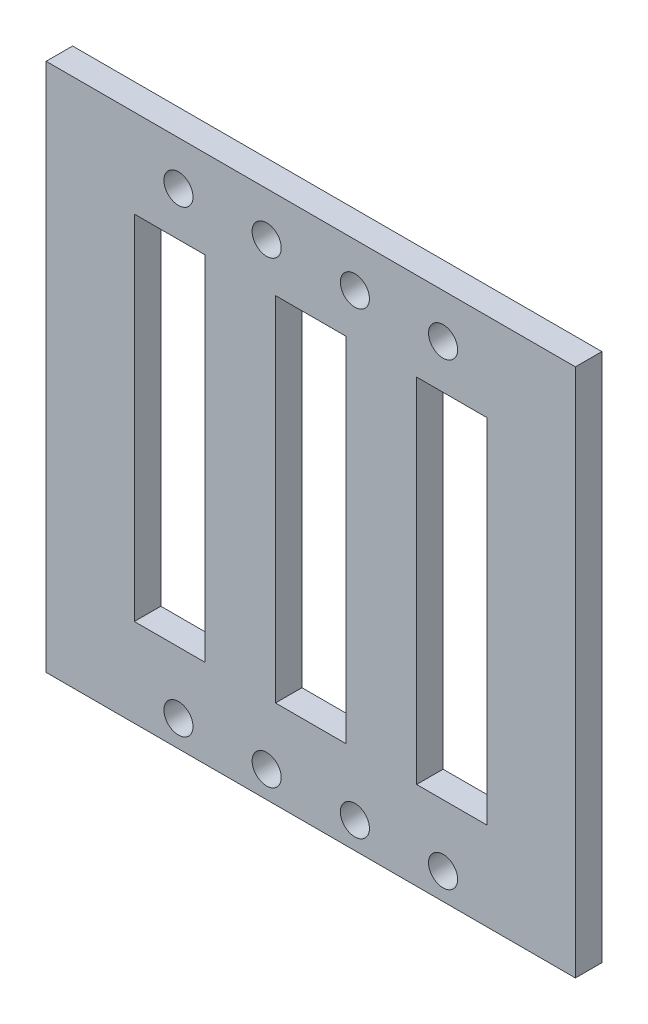
SolidWorks part; units mm, degrees
ref_plane "Plan de face" through (0, 0, 0) normal (0, 0, 1) x (1, 0, 0)
ref_plane "Plan de dessus" through (0, 0, 0) normal (0, 1, 0) x (1, 0, 0)
ref_plane "Plan de droite" through (0, 0, 0) normal (1, 0, 0) x (0, 0, -1)
sketch "Esquisse1" plane through (0, 0, 0) normal (0, 0, 1) x (1, 0, 0)
  line L1 (-30, -30) -> (30, -30)
  line L2 (-30, -30) -> (-30, 30)
  line L3 (-30, 30) -> (30, 30)
  line L4 (30, -30) -> (30, 30)
  line L5 (-30, -30) -> (30, 30) construction
  line L6 (-30, 30) -> (30, -30) construction
  circle A0 centre (-15, 25) radius 1.65
  circle A1 centre (5, 25) radius 1.65
  circle A2 centre (15, 25) radius 1.65
  circle A3 centre (-5, 25) radius 1.65
  circle A4 centre (-15, -27) radius 1.65
  circle A5 centre (-5, -27) radius 1.65
  circle A6 centre (5, -27) radius 1.65
  circle A7 centre (15, -27) radius 1.65
  point P0 (0, 0)
  dimension "D3" = 3.3
  dimension "D4" = 3.3
  dimension "D5" = 3.3
  dimension "D6" = 3.3
  dimension "D7" = 3.3
  dimension "D8" = 3.3
  dimension "D9" = 3.3
  dimension "D10" = 5
  dimension "D22" = 3.3
  dimension "D1" = 60
  dimension "D2" = 60
  dimension "D11" = 15
  dimension "D12" = 10
  dimension "D13" = 10
  dimension "D14" = 15
  dimension "D15" = 3
  dimension "D16" = 3
  dimension "D17" = 3
  dimension "D18" = 3
  dimension "D19" = 15
  dimension "D20" = 10
  dimension "D21" = 15
  dimension "D23" = 10
  dimension "D24" = 5
  dimension "D25" = 5
  dimension "D26" = 5
extrude "Boss.-Extru.1" add sketch "Esquisse1" against normal blind 3
sketch "Esquisse2" plane through (0, 0, 0) normal (0, 0, 1) x (1, 0, 0)
  line L0 (-30, 30) -> (-30, -30) construction
  line L1 (-20, 20) -> (-12, 20)
  line L2 (-20, 20) -> (-20, -20)
  line L3 (-20, -20) -> (-12, -20)
  line L4 (-12, 20) -> (-12, -20)
  line L5 (-20, 20) -> (-12, -20) construction
  line L6 (-20, -20) -> (-12, 20) construction
  line L7 (-4, -20) -> (4, -20)
  line L8 (-4, -20) -> (-4, 20)
  line L9 (-4, 20) -> (4, 20)
  line L10 (4, -20) -> (4, 20)
  line L11 (-4, -20) -> (4, 20) construction
  line L12 (-4, 20) -> (4, -20) construction
  line L13 (12, -20) -> (20, -20)
  line L14 (12, -20) -> (12, 20)
  line L15 (12, 20) -> (20, 20)
  line L16 (20, -20) -> (20, 20)
  line L17 (12, -20) -> (20, 20) construction
  line L18 (12, 20) -> (20, -20) construction
  line L19 (30, -30) -> (30, 30) construction
  line L20 (-30, -30) -> (30, -30) construction
  point P0 (-16, 0)
  point P5 (0, 0)
  point P11 (16, 0)
  point P22 (0, -30)
  dimension "D1" = 10
  dimension "D2" = 10
  dimension "D3" = 8
  dimension "D4" = 8
  dimension "D5" = 8
  dimension "D6" = 10
  dimension "D7" = 40
  dimension "D8" = 10
  dimension "D9" = 10
  dimension "D10" = 40
extrude "Enlèv. mat.-Extru.1" cut sketch "Esquisse2" against normal blind 3
